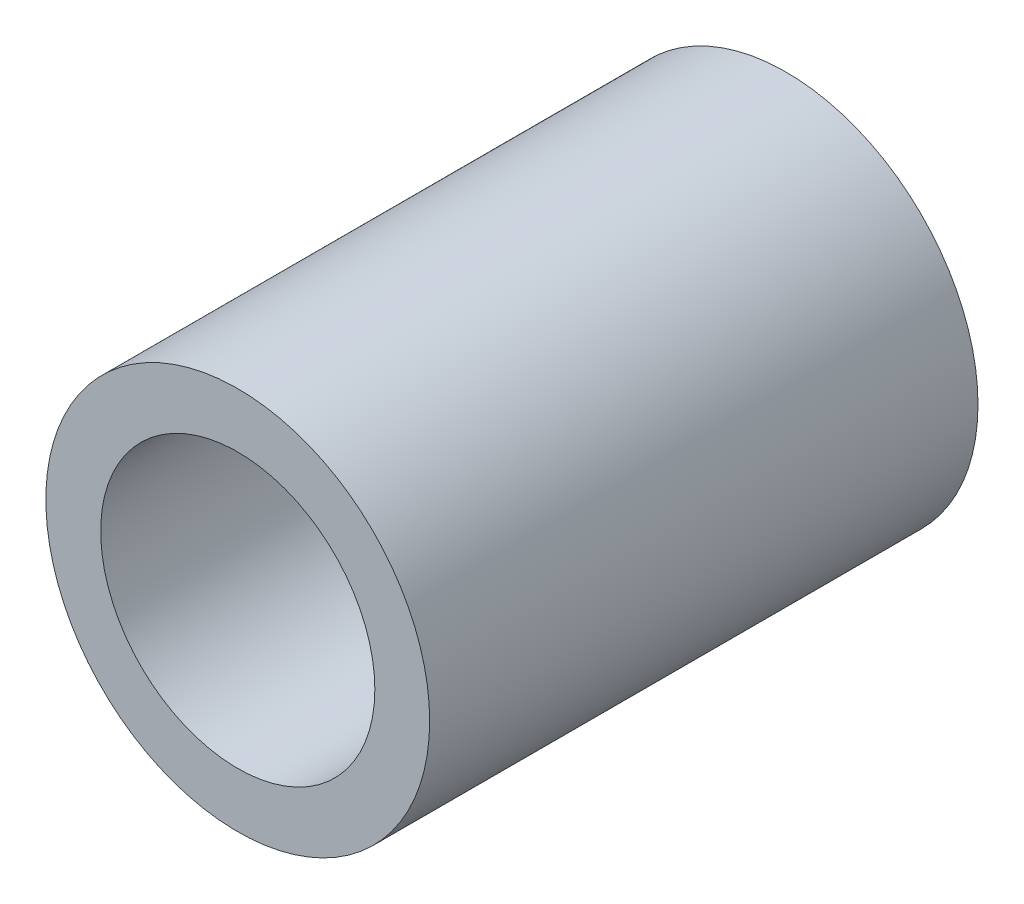
SolidWorks part; units mm, degrees
ref_plane "face" through (0, 0, 0) normal (0, 0, 1) x (1, 0, 0)
ref_plane "dessus" through (0, 0, 0) normal (0, 1, 0) x (1, 0, 0)
ref_plane "droite" through (0, 0, 0) normal (1, 0, 0) x (0, 0, -1)
sketch "Esquisse1" plane through (0, 0, 0) normal (0, 0, 1) x (1, 0, 0)
  circle A0 centre (0, 0) radius 14
  circle A1 centre (0, 0) radius 10
  dimension "D1" = 20
  dimension "D2" = 28
extrude "Base-Extrusion" add sketch "Esquisse1" along normal blind 40
ref_plane "Plan1" through (0, 0, 20) normal (0, 0, 1) x (1, 0, 0)
